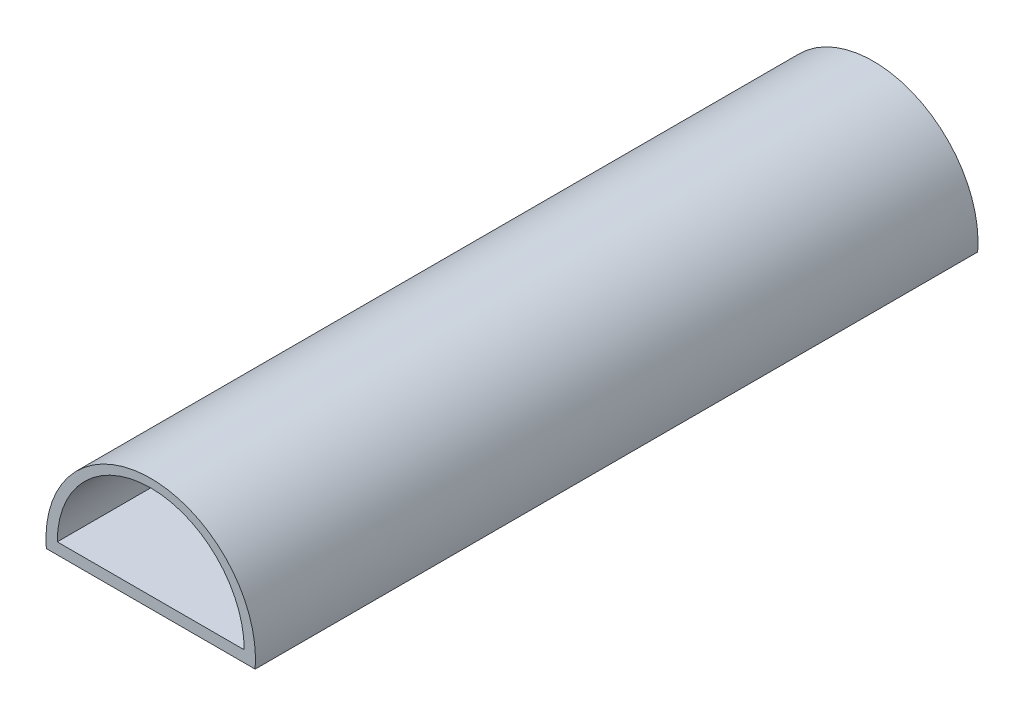
SolidWorks part; units mm, degrees
material "PVC 0.007 Plasticized"
ref_plane "Front Plane" through (0, 0, 0) normal (0, 0, 1) x (1, 0, 0)
ref_plane "Top Plane" through (0, 0, 0) normal (0, 1, 0) x (1, 0, 0)
ref_plane "Right Plane" through (0, 0, 0) normal (1, 0, 0) x (0, 0, -1)
sketch "Sketch1" plane through (0, 0, 0) normal (0, 0, 1) x (1, 0, 0)
  line L0 (-23.1114, -10.0484) -> (6.2574, -10.0484)
  line L2 (-8.427, -8.4609) -> (-21.5715, -8.4609)
  line L3 (-8.427, -8.4609) -> (4.7175, -8.4609)
  arc A0 (-23.1114, -10.0484) -> (6.2574, -10.0484) centre (-8.427, -8.8769) cw
  arc A1 (-21.5715, -8.4609) -> (4.7175, -8.4609) centre (-8.427, -8.4609) cw
extrude "Boss-Extrude2" add sketch "Sketch1" along normal blind 101.6
